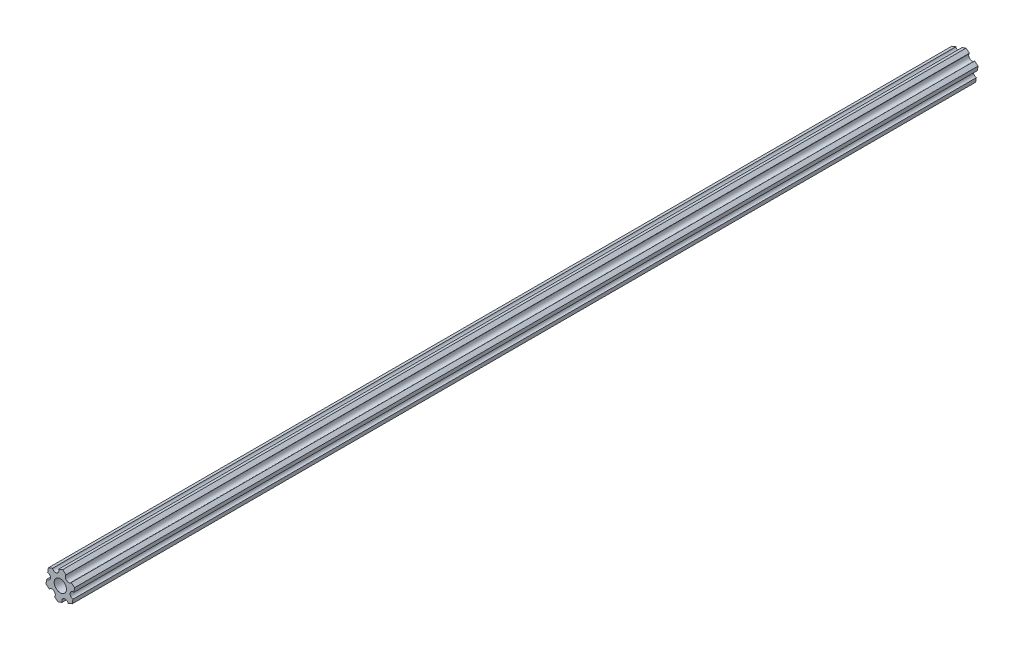
SolidWorks part; units mm, degrees
ref_plane "Front Plane" through (0, 0, 0) normal (0, 0, 1) x (1, 0, 0)
ref_plane "Top Plane" through (0, 0, 0) normal (0, 1, 0) x (1, 0, 0)
ref_plane "Right Plane" through (0, 0, 0) normal (1, 0, 0) x (0, 0, -1)
sketch "Sketch1" plane through (0, 0, 0) normal (0, 0, 1) x (1, 0, 0)
  line L0 (-3.7661, 5.3534) -> (-5.7055, 4.6054)
  line L1 (1.1357, 7.2439) -> (-0.8038, 6.4959)
  line L2 (-5.7055, 4.6054) -> (-6.0275, 2.5519)
  line L3 (-6.8412, -2.6384) -> (-5.2237, -3.944)
  line L4 (-1.1357, -7.2439) -> (0.8038, -6.4959)
  line L5 (5.7055, -4.6054) -> (6.0275, -2.5519)
  line L6 (6.8412, 2.6384) -> (5.2237, 3.944)
  line L7 (2.7531, 5.9383) -> (1.1357, 7.2439)
  line L8 (6.5193, 0.5848) -> (6.8412, 2.6384)
  line L9 (3.7661, -5.3534) -> (5.7055, -4.6054)
  line L10 (-2.7531, -5.9383) -> (-1.1357, -7.2439)
  line L11 (-6.5193, -0.5848) -> (-6.8412, -2.6384)
  arc A0 (-3.6831, 5.1728) -> (-5.8334, 2.5088) centre (0, 0) ccw construction
  arc A1 (-3.7661, 5.3534) -> (-0.8038, 6.4959) centre (-2.2849, 5.9247) ccw
  circle A2 centre (0, 0) radius 2.9337
  arc A3 (2.7531, 5.9383) -> (5.2237, 3.944) centre (3.9884, 4.9411) ccw
  arc A4 (6.5193, 0.5848) -> (6.0275, -2.5519) centre (6.2734, -0.9835) ccw
  arc A5 (3.7661, -5.3534) -> (0.8038, -6.4959) centre (2.2849, -5.9247) ccw
  arc A6 (-2.7531, -5.9383) -> (-5.2237, -3.944) centre (-3.9884, -4.9411) ccw
  arc A7 (-6.5193, -0.5848) -> (-6.0275, 2.5519) centre (-6.2734, 0.9835) ccw
  arc A8 (2.6382, 5.776) -> (-0.744, 6.3063) centre (0, 0) ccw construction
  arc A9 (6.3213, 0.6033) -> (5.0894, 3.7974) centre (0, 0) ccw construction
  arc A10 (3.6831, -5.1728) -> (5.8334, -2.5088) centre (0, 0) ccw construction
  arc A11 (-2.6382, -5.776) -> (0.744, -6.3063) centre (0, 0) ccw construction
  arc A12 (-6.3213, -0.6033) -> (-5.0894, -3.7974) centre (0, 0) ccw construction
  point P25 (0, 0)
  dimension "D2" = 3.175
  dimension "D3" = 5.8674
  dimension "D1" = 12.7
  dimension "D4" = 6
extrude "Boss-Extrude1" add sketch "Sketch1" along normal blind 431.8
